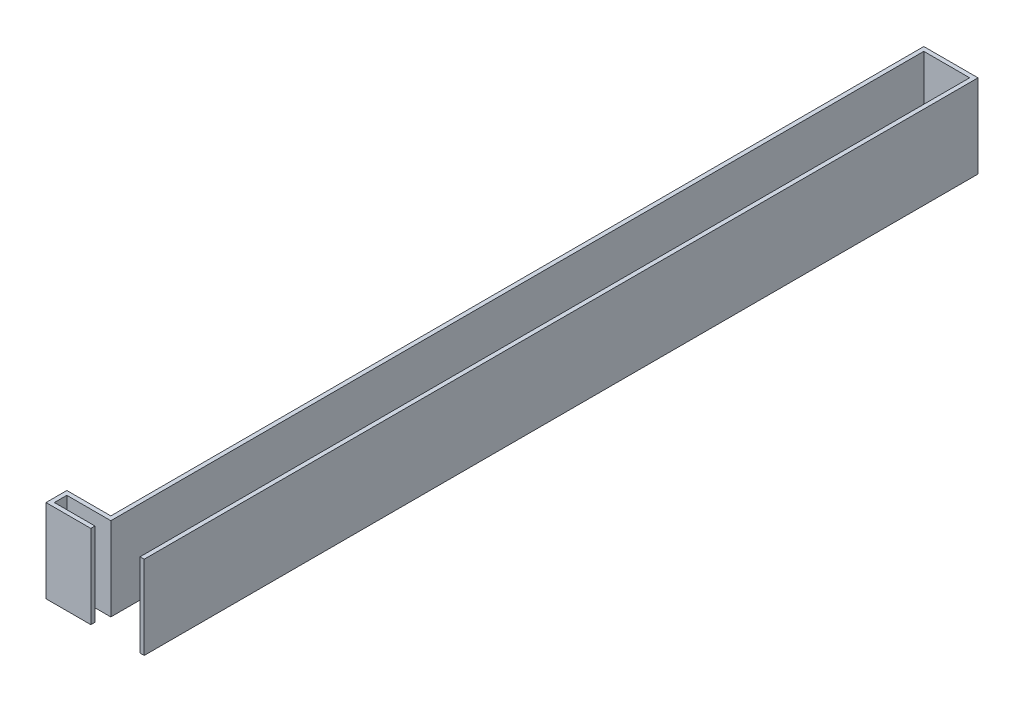
SolidWorks part; units mm, degrees
ref_plane "Front Plane" through (0, 0, 0) normal (0, 0, 1) x (1, 0, 0)
ref_plane "Top Plane" through (0, 0, 0) normal (0, 1, 0) x (1, 0, 0)
ref_plane "Right Plane" through (0, 0, 0) normal (1, 0, 0) x (0, 0, -1)
sketch "Sketch2" plane through (0, 0, 0) normal (0, 1, 0) x (1, 0, 0)
  line L0 (0, 0) -> (0, 2000)
  line L1 (0, 2000) -> (-130, 2000)
  line L2 (-130, 2000) -> (-130, 50)
  line L3 (-130, 50) -> (-235.5, 50)
  line L4 (-235.5, 50) -> (-235.5, 40)
  line L5 (-225.5, 40) -> (-120, 40)
  line L6 (-120, 40) -> (-120, 1990)
  line L7 (-120, 1990) -> (-10, 1990)
  line L8 (-10, 1990) -> (-10, 2)
  line L9 (-128, 10) -> (-225.5, 10)
  line L10 (-235.5, 10) -> (-235.5, 0)
  line L11 (-235.5, 0) -> (-128, 0)
  line L12 (-235.5, 40) -> (-235.5, 10)
  line L13 (-225.5, 40) -> (-225.5, 10)
  line L14 (-128, 10) -> (-128, 0)
  line L15 (-10, 2) -> (-10, 0)
  line L16 (-10, 0) -> (0, 0)
  point P3 (-130, 1025)
  dimension "D1" = 10
  dimension "D2" = 10
  dimension "D3" = 10
  dimension "D4" = 10
  dimension "D5" = 10
  dimension "D6" = 2000
  dimension "D7" = 130
  dimension "D8" = 1950
  dimension "D9" = 105.5
  dimension "D10" = 10
  dimension "D11" = 10
  dimension "D12" = 10
extrude "Boss-Extrude1" add sketch "Sketch2" along normal blind 200
